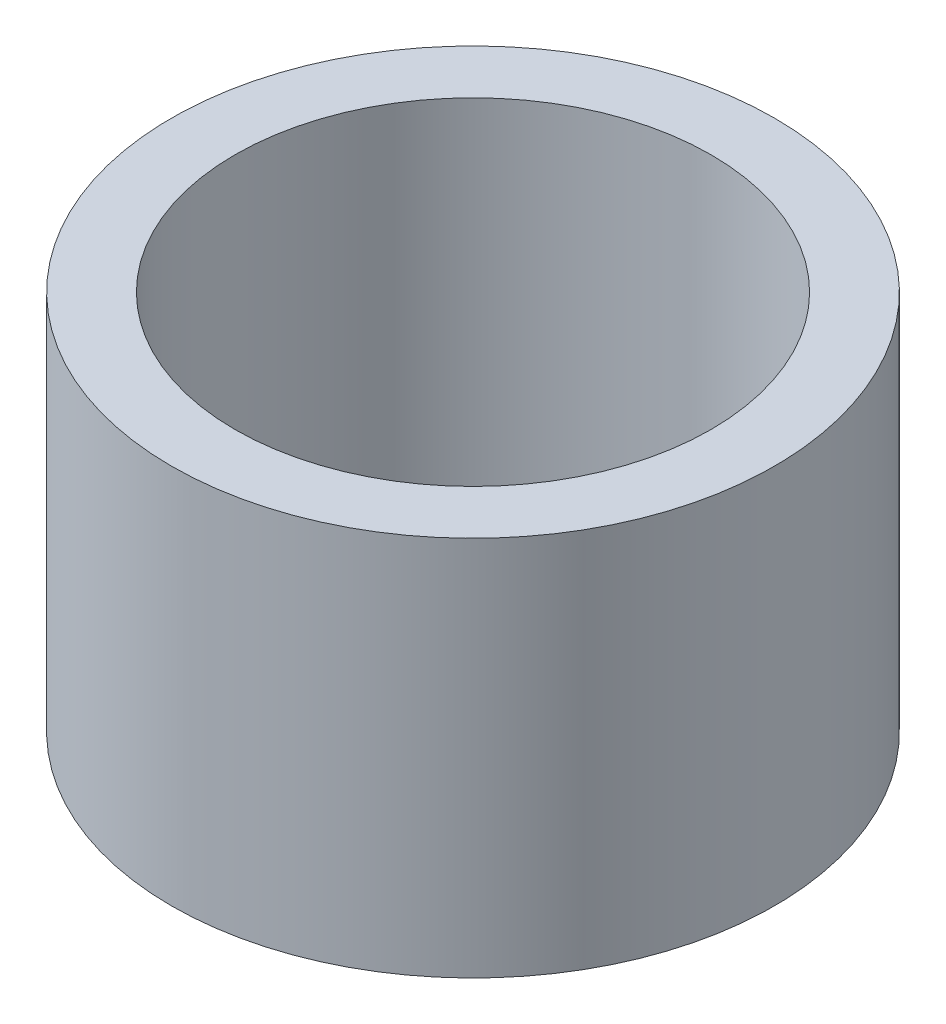
SolidWorks part; units mm, degrees
material "6061 合金"
ref_plane "前视基准面" through (0, 0, 0) normal (0, 0, 1) x (1, 0, 0)
ref_plane "上视基准面" through (0, 0, 0) normal (0, 1, 0) x (1, 0, 0)
ref_plane "右视基准面" through (0, 0, 0) normal (1, 0, 0) x (0, 0, -1)
sketch "草图1" plane through (0, 0, 0) normal (0, 1, 0) x (1, 0, 0)
  circle A0 centre (0, 0) radius 9.5
  circle A1 centre (0, 0) radius 7.5
  dimension "D1" = 19
  dimension "D2" = 15
extrude "凸台-拉伸1" add sketch "草图1" along normal blind 12
